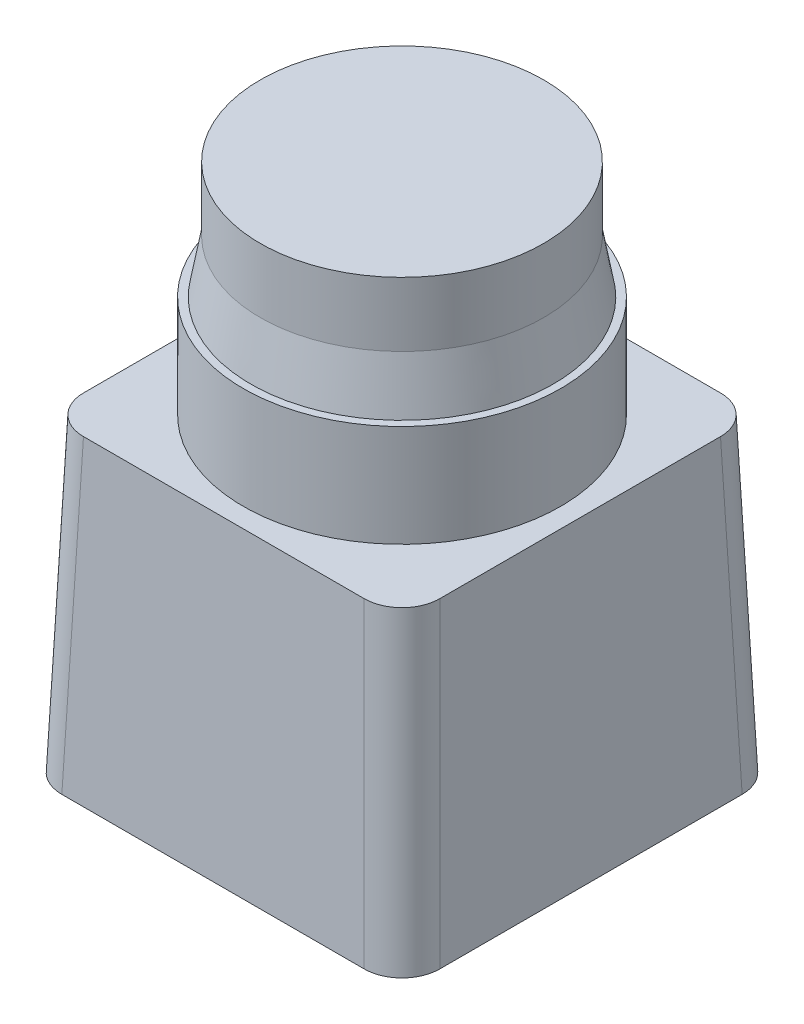
SolidWorks part; units mm, degrees
ref_plane "Plano frontal" through (0, 0, 0) normal (0, 0, 1) x (1, 0, 0)
ref_plane "Plano superior" through (0, 0, 0) normal (0, 1, 0) x (1, 0, 0)
ref_plane "Plano direito" through (0, 0, 0) normal (1, 0, 0) x (0, 0, -1)
sketch "Esboço1" plane through (0, 0, 0) normal (0, 1, 0) x (1, 0, 0)
  line L1 (-25, 25) -> (25, 25)
  line L2 (-25, 25) -> (-25, -25)
  line L3 (-25, -25) -> (25, -25)
  line L4 (25, 25) -> (25, -25)
  line L5 (-25, 25) -> (25, -25) construction
  line L6 (-25, -25) -> (25, 25) construction
  point P0 (0, 0)
  dimension "D1" = 50
  dimension "D2" = 50
extrude "Ressalto-extrusão1" add sketch "Esboço1" along normal blind 41 draft 2
sketch "Esboço2" plane through (0, 0, 0) normal (1, 0, 0) x (0, 0, -1)
  line L0 (0, 41) -> (0, 70) construction
  line L1 (-23.5682, 41) -> (23.5682, 41) construction
  line L2 (0, 70) -> (18.75, 70)
  line L3 (18.75, 70) -> (18.75, 61.5)
  line L4 (18.75, 61.5) -> (20, 54.5)
  line L5 (21, 41) -> (21, 54.5)
  line L6 (20, 54.5) -> (21, 54.5)
  line L7 (0, 41) -> (21, 41)
  line L8 (21, 41) -> (0, 41)
  dimension "D1" = 29
  dimension "D2" = 40
  dimension "D3" = 37.5
  dimension "D4" = 42
  dimension "D5" = 20.5
  dimension "D6" = 13.5
revolve "Revolução1" add sketch "Esboço2" angle 360 about L0
fillet "Filete1" radius 5 4 edges at (-24.2841, 20.5, 24.2841) (-24.2841, 20.5, -24.2841) (24.2841, 20.5, 24.2841) (24.2841, 20.5, -24.2841)
sketch "Esboço3" plane through (0, 0, 0) normal (0, -1, 0) x (-1, 0, 0)
  line L0 (-20, -19.375) -> (-25, -19.375) construction
  line L1 (-25, -20.003) -> (-25, 20.003) construction
  line L2 (20, 20.625) -> (25, 20.625) construction
  line L3 (25, 20.003) -> (25, -20.003) construction
  line L4 (-20, -20.625) -> (-20, -25) construction
  line L5 (20.003, -25) -> (-20.003, -25) construction
  line L6 (20, 20.625) -> (20, 25) construction
  line L7 (-20.003, 25) -> (20.003, 25) construction
  circle A0 centre (20, 20.625) radius 1.25
  circle A1 centre (-20, -19.375) radius 1.25
  dimension "D1" = 2.5
  dimension "D2" = 2.5
  dimension "D3" = 40
  dimension "D4" = 40
extrude "Corte-extrusão1" cut sketch "Esboço3" against normal blind 6
cosmetic thread "Representação de rosca1" parameters "D2"=3
cosmetic thread "Representação de rosca2" parameters "D2"=3
sketch "Esboço4" plane through (0, 41, 0) normal (0, 1, 0) x (1, 0, 0)
  circle A0 centre (0, 0) radius 19.9823
sketch "Esboço5" plane through (0, 0, 0) normal (1, 0, 0) x (0, 0, -1)
  line L0 (19.0179, 60) -> (22, 60)
  line L1 (20, 54.5) -> (18.75, 61.5) construction
  line L2 (22, 60) -> (22, 41)
  line L3 (19.9823, 41) -> (-19.9823, 41) construction
  line L4 (21, 41) -> (21, 54.5) construction
  line L5 (22, 41) -> (21, 41)
  line L6 (21, 41) -> (21, 54.5) construction
  line L7 (19.0179, 60) -> (20, 54.5)
  line L8 (20, 54.5) -> (21, 54.5)
  line L9 (21, 54.5) -> (21, 41)
  point P5 (0, 0)
  point P13 (20, 54.5)
  dimension "D1" = 19
  dimension "D2" = 1
revolve "Revolução2" add sketch "Esboço5" angle 10 about axis through (0, 41, 0) along (0, -1, 0) other way angle 10
ref_plane "Plano1" through (-25, 0, 0) normal (1, 0, 0) x (0, 0, -1)
sketch "Esboço7" plane through (-25, 0, 0) normal (1, 0, 0) x (0, 0, -1)
  line L0 (-13.6, 8.9) -> (-13.6, 4.9) construction
  line L1 (-16.1, 8.9) -> (-11.1, 8.9)
  line L2 (-17.1, 7.9) -> (-17.1, 5.9)
  line L3 (-16.1, 4.9) -> (-11.1, 4.9)
  line L4 (-10.1, 7.9) -> (-10.1, 5.9)
  line L5 (-17.1, 6.9) -> (-10.1, 6.9) construction
  line L6 (-20.003, 0) -> (20.003, 0) construction
  line L7 (0, 54.5) -> (0, 41) construction
  arc A0 (-17.1, 5.9) -> (-16.1, 4.9) centre (-16.1, 5.9) ccw
  arc A1 (-11.1, 4.9) -> (-10.1, 5.9) centre (-11.1, 5.9) ccw
  arc A2 (-11.1, 8.9) -> (-10.1, 7.9) centre (-11.1, 7.9) cw
  arc A3 (-16.1, 8.9) -> (-17.1, 7.9) centre (-16.1, 7.9) ccw
  point P14 (-17.1, 4.9)
  point P19 (-10.1, 8.9)
  point P22 (-17.1, 8.9)
  dimension "D5" = 1
  dimension "D1" = 6.9
  dimension "D2" = 13.6
  dimension "D3" = 7
  dimension "D4" = 4
extrude "Corte-extrusão2" cut sketch "Esboço7" along normal blind 5
